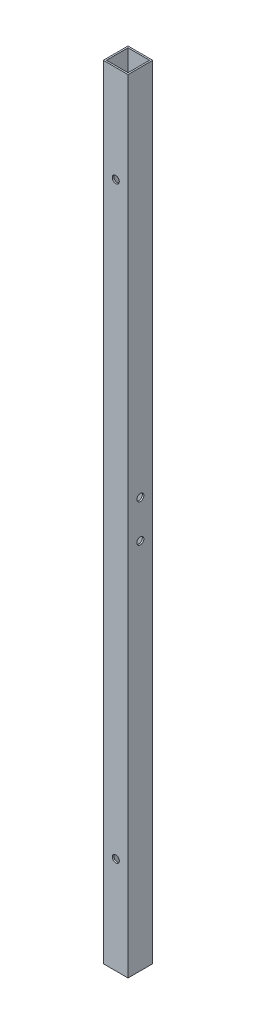
SolidWorks part; units mm, degrees
ref_plane "Front Plane" through (0, 0, 0) normal (0, 0, 1) x (1, 0, 0)
ref_plane "Top Plane" through (0, 0, 0) normal (0, 1, 0) x (1, 0, 0)
ref_plane "Right Plane" through (0, 0, 0) normal (1, 0, 0) x (0, 0, -1)
sketch "Sketch1" plane through (0, 0, 0) normal (0, 1, 0) x (1, 0, 0)
  line L0 (-6.9, -6.9) -> (-6.9, 6.9)
  line L1 (-7.9, -7.9) -> (7.9, -7.9)
  line L2 (-7.9, -7.9) -> (-7.9, 7.9)
  line L3 (-7.9, 7.9) -> (7.9, 7.9)
  line L4 (7.9, -7.9) -> (7.9, 7.9)
  line L5 (-7.9, -7.9) -> (7.9, 7.9) construction
  line L6 (-7.9, 7.9) -> (7.9, -7.9) construction
  line L7 (-6.9, 6.9) -> (6.9, 6.9)
  line L8 (6.9, -6.9) -> (6.9, 6.9)
  line L9 (-6.9, -6.9) -> (6.9, -6.9)
  point P0 (0, 0)
  dimension "D1" = 1
extrude "Boss-Extrude2" add sketch "Sketch1" along normal blind 500
sketch "Sketch4" plane through (0, 0, -7.9) normal (0, 0, -1) x (-1, 0, 0)
  circle A1 centre (-0.0943, 438) radius 2.25
  circle A2 centre (-0.0943, 62) radius 2.25
  dimension "D1" = 376
  dimension "D4" = 4.5
  dimension "D2" = 4.5
extrude "Cut-Extrude2" cut sketch "Sketch4" against normal through all
sketch "Sketch6" plane through (7.9, 0, 0) normal (1, 0, 0) x (0, 0, -1)
  line L0 (-7.9, 250) -> (7.9, 250) construction
  line L1 (-7.9, 500) -> (-7.9, 0) construction
  line L2 (7.9, 500) -> (7.9, 0) construction
  line L3 (7.9, 435.75) -> (7.9, 440.25) construction
  circle A0 centre (0, 262) radius 2.25
  circle A1 centre (0, 238) radius 2.25
  dimension "D1" = 4.5
  dimension "D3" = 4.5
  dimension "D4" = 12
  dimension "D2" = 24
extrude "Cut-Extrude3" cut sketch "Sketch6" against normal through all
